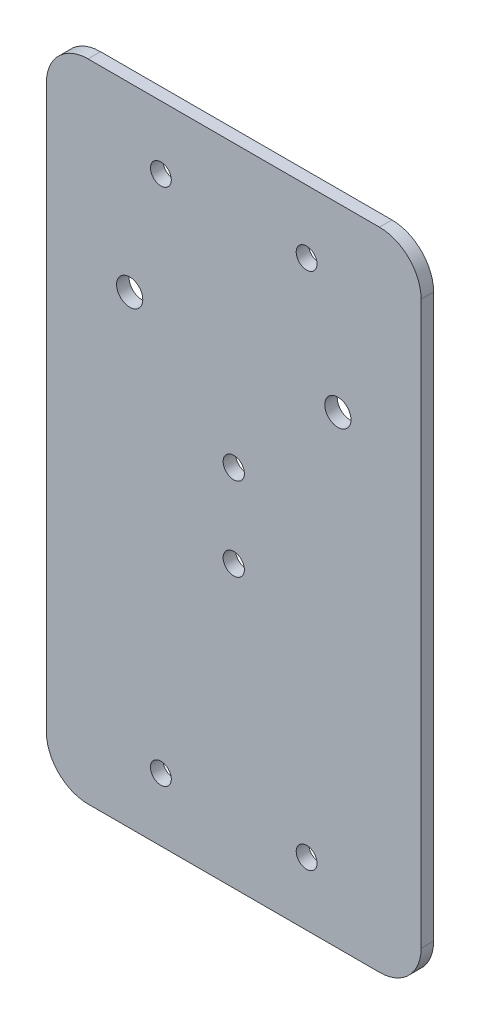
SolidWorks part; units mm, degrees
ref_plane "Front Plane" through (0, 0, 0) normal (0, 0, 1) x (1, 0, 0)
ref_plane "Top Plane" through (0, 0, 0) normal (0, 1, 0) x (1, 0, 0)
ref_plane "Right Plane" through (0, 0, 0) normal (1, 0, 0) x (0, 0, -1)
sketch "Croquis1" plane through (0, 0, 0) normal (0, 0, 1) x (1, 0, 0)
  line L0 (-1000, 0) -> (49000, 0) construction
  line L1 (0, -1000) -> (0, 49000) construction
  line L3 (35, 77.5) -> (-35, 77.5)
  line L4 (45, 67.5) -> (45, -67.5)
  line L5 (35, -77.5) -> (-35, -77.5)
  line L6 (-45, 67.5) -> (-45, -67.5)
  line L7 (45, 77.5) -> (-45, -77.5) construction
  line L8 (45, -77.5) -> (-45, 77.5) construction
  circle A0 centre (17.5, 62.325) radius 2.5
  circle A1 centre (17.5, -62.325) radius 2.5
  circle A2 centre (-17.5, -62.325) radius 2.5
  circle A3 centre (-17.5, 62.325) radius 2.5
  circle A4 centre (0, 10) radius 2.55
  circle A5 centre (0, -10) radius 2.55
  arc A6 (45, -67.5) -> (35, -77.5) centre (35, -67.5) cw
  arc A7 (-35, -77.5) -> (-45, -67.5) centre (-35, -67.5) cw
  arc A8 (35, 77.5) -> (45, 67.5) centre (35, 67.5) cw
  arc A9 (-35, 77.5) -> (-45, 67.5) centre (-35, 67.5) ccw
  circle A10 centre (-25, 34) radius 3.15
  circle A11 centre (25, 34) radius 3.15
  point P13 (0, 0)
  dimension "D1" = 5
  dimension "D2" = 124.65
  dimension "D3" = 35
  dimension "D4" = 5.1
  dimension "D5" = 20
  dimension "D8" = 10
  dimension "D9" = 43.5
  dimension "D10" = 6.3
  dimension "D11" = 50
  dimension "D6" = 155
  dimension "D7" = 90
extrude "Saliente-Extruir1" add sketch "Croquis1" along normal blind 3
